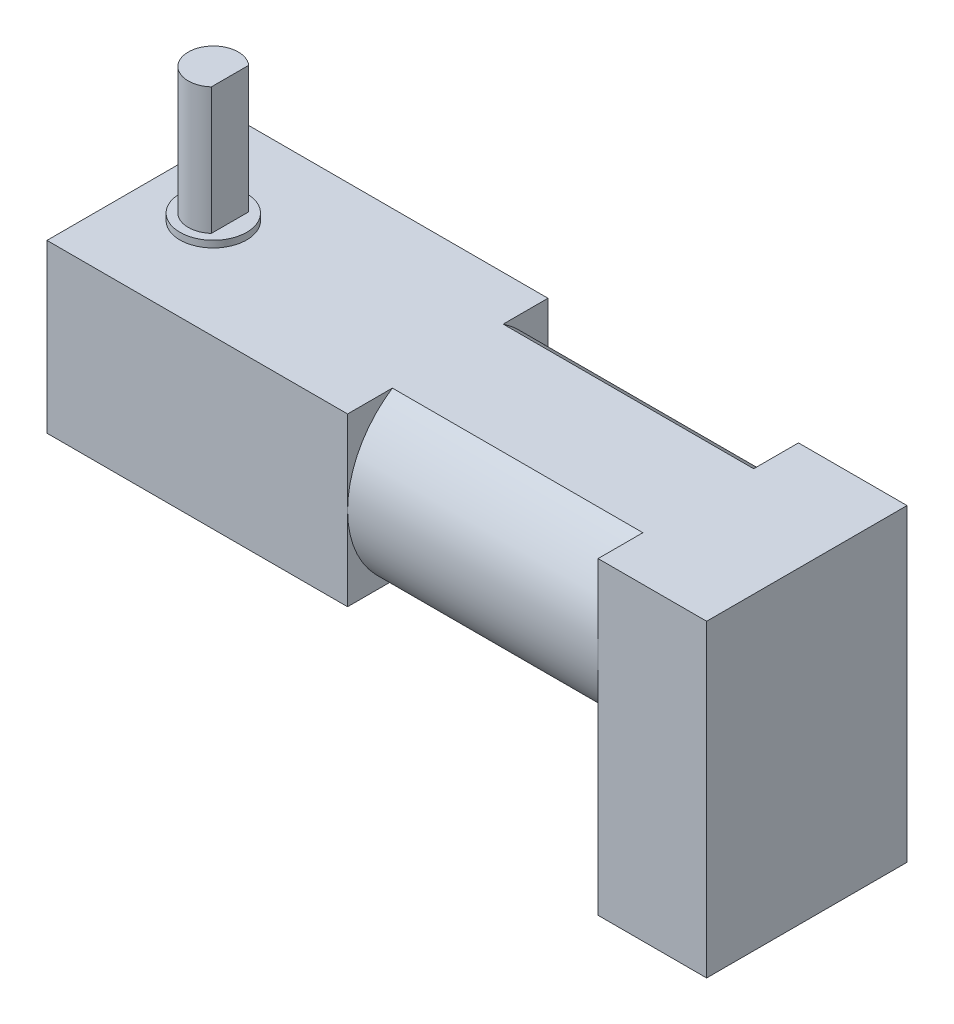
SolidWorks part; units mm, degrees
ref_plane "前视基准面" through (0, 0, 0) normal (0, 0, 1) x (1, 0, 0)
ref_plane "上视基准面" through (0, 0, 0) normal (0, 1, 0) x (1, 0, 0)
ref_plane "右视基准面" through (0, 0, 0) normal (1, 0, 0) x (0, 0, -1)
other "Configuration Table"
sketch "草图1" plane through (0, 0, 0) normal (0, 1, 0) x (1, 0, 0)
  line L1 (0, 0) -> (18, 0)
  line L2 (0, 0) -> (0, 12)
  line L3 (0, 12) -> (18, 12)
  line L4 (18, 0) -> (18, 12)
  line L5 (0, 0) -> (18, 12) construction
  line L6 (0, 12) -> (18, 0) construction
  point P4 (9, 6)
  dimension "D1" = 18
  dimension "D2" = 12
extrude "凸台-拉伸1" add sketch "草图1" along normal blind 10
sketch "草图2" plane through (18, 0, 0) normal (1, 0, 0) x (0, 0, -1)
  line L0 (0, 10) -> (12, 0) construction
  line L1 (2.6834, 10) -> (9.3166, 10)
  line L2 (0, 10) -> (12, 10) construction
  line L3 (2.6834, 0) -> (9.3166, 0)
  line L4 (0, 0) -> (12, 0) construction
  arc A0 (2.6834, 10) -> (2.6834, 0) centre (6, 5) ccw
  arc A1 (9.3166, 0) -> (9.3166, 10) centre (6, 5) ccw
  dimension "D1" = 6
extrude "凸台-拉伸2" add sketch "草图2" along normal blind 15
sketch "草图3" plane through (0, 10, 0) normal (0, 1, 0) x (1, 0, 0)
  line L0 (0, 6) -> (33, 6) construction
  line L1 (0, 12) -> (0, 0) construction
  line L2 (33, 9.3166) -> (33, 2.6834) construction
  circle A0 centre (3.96, 6) radius 2
  point P8 (3.4042, 6)
  dimension "D1" = 4
  dimension "D2" = 3.96
extrude "凸台-拉伸3" add sketch "草图3" along normal blind 0.4
sketch "草图4" plane through (0, 10.4, 0) normal (0, 1, 0) x (1, 0, 0)
  line L0 (4.96, 4.882) -> (4.96, 7.118)
  arc A0 (4.96, 7.118) -> (4.96, 4.882) centre (3.96, 6) ccw
  dimension "D1" = 3
  dimension "D2" = 1
extrude "凸台-拉伸5" add sketch "草图4" along normal offset from surface (7.6 mm away) 8 up to face at (3.96, 10, -8) offset beyond the face yes
sketch "草图5" plane through (33, 0, 0) normal (1, 0, 0) x (0, 0, -1)
  line L1 (0, 10) -> (12, 10)
  line L2 (0, 10) -> (0, -8.5)
  line L3 (0, -8.5) -> (12, -8.5)
  line L4 (12, 10) -> (12, -8.5)
  line L5 (0, 10) -> (12, -8.5) construction
  line L6 (0, -8.5) -> (12, 10) construction
  point P4 (6, 0.75)
  point P6 (12, 10)
  dimension "D1" = 18.5
extrude "凸台-拉伸6" add sketch "草图5" along normal blind 6.5
